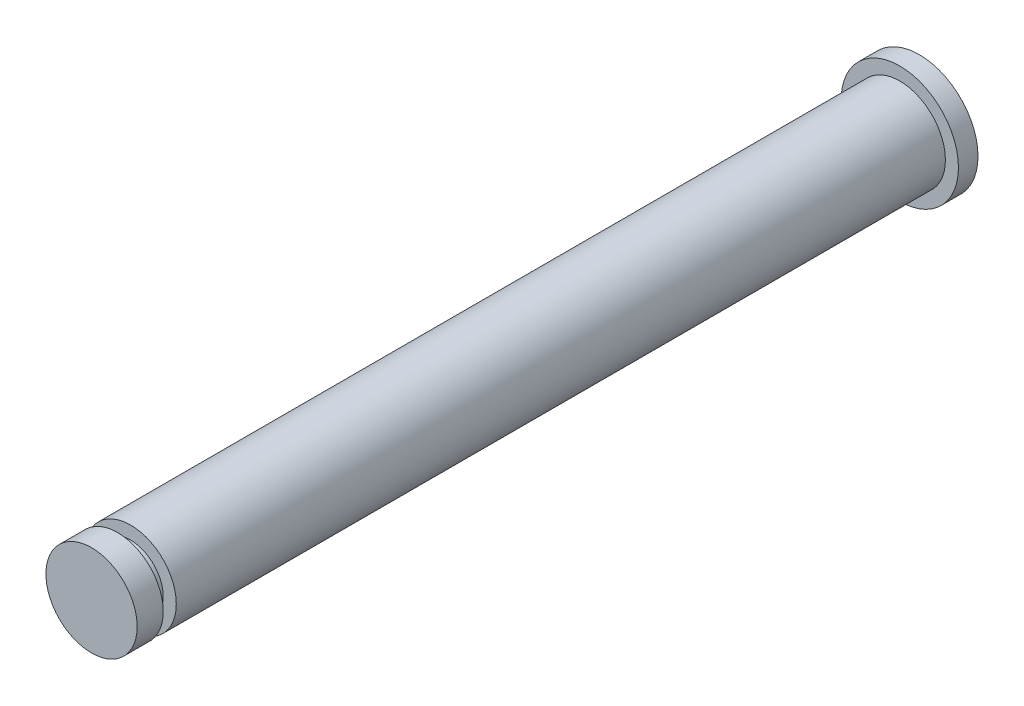
SolidWorks part; units mm, degrees
material "普通碳钢"
ref_plane "前视基准面" through (0, 0, 0) normal (0, 0, 1) x (1, 0, 0)
ref_plane "上视基准面" through (0, 0, 0) normal (0, 1, 0) x (1, 0, 0)
ref_plane "右视基准面" through (0, 0, 0) normal (1, 0, 0) x (0, 0, -1)
sketch "草图2" plane through (0, 0, 0) normal (1, 0, 0) x (0, 0, -1)
  line L0 (0, 0) -> (69.1548, 0) construction
  line L1 (0, 0) -> (0, 3.5)
  line L2 (0, 3.5) -> (2, 3.5)
  line L3 (63.5, 4.5) -> (63.5, 0)
  line L4 (3, 3.5) -> (62, 3.5)
  line L5 (0, 0) -> (-13.2853, 0) construction
  line L6 (2, 3.5) -> (2, 2.5)
  line L7 (2, 2.5) -> (3, 2.5)
  line L8 (3, 3.5) -> (3, 2.5)
  line L9 (0, 0) -> (63.5, 0)
  line L10 (62, 3.5) -> (62, 4.5)
  line L11 (62, 4.5) -> (63.5, 4.5)
  dimension "D1" = 7
  dimension "D2" = 2
  dimension "D3" = 59
  dimension "D4" = 1
  dimension "D5" = 1
  dimension "D6" = 1.5
  dimension "D7" = 1
revolve "旋转1" add sketch "草图2" angle 360 about L0
move or copy body "实体-移动/复制1" [suppressed] bodies to move or copy 106
